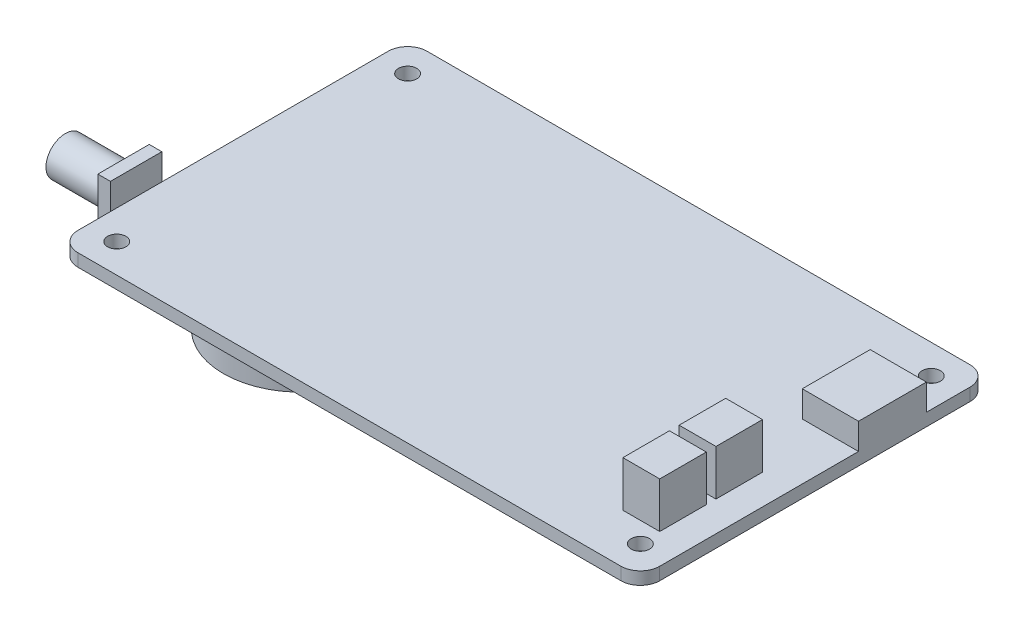
SolidWorks part; units mm, degrees
ref_plane "Front Plane" through (0, 0, 0) normal (0, 0, 1) x (1, 0, 0)
ref_plane "Top Plane" through (0, 0, 0) normal (0, 1, 0) x (1, 0, 0)
ref_plane "Right Plane" through (0, 0, 0) normal (1, 0, 0) x (0, 0, -1)
sketch "Sketch1" plane through (0, 0, 0) normal (0, 1, 0) x (1, 0, 0)
  line L1 (-38.1, 22.86) -> (38.1, 22.86)
  line L2 (-38.1, 22.86) -> (-38.1, -22.86)
  line L3 (-38.1, -22.86) -> (38.1, -22.86)
  line L4 (38.1, 22.86) -> (38.1, -22.86)
  line L5 (-38.1, 22.86) -> (38.1, -22.86) construction
  line L6 (-38.1, -22.86) -> (38.1, 22.86) construction
  point P0 (0, 0)
  dimension "D1" = 76.2
  dimension "D2" = 45.72
extrude "Boss-Extrude1" add sketch "Sketch1" along normal mid plane 1.651
sketch "Sketch2" plane through (0, -0.8255, 0) normal (0, -1, 0) x (1, 0, 0)
  line L0 (-19.05, 22.86) -> (-19.05, -22.86) construction
  line L1 (-38.1, 22.86) -> (38.1, 22.86) construction
  line L2 (38.1, -22.86) -> (-38.1, -22.86) construction
  line L3 (-38.1, -22.86) -> (-38.1, 22.86) construction
  line L4 (-38.1, 10.16) -> (38.1, 10.16) construction
  line L5 (38.1, 22.86) -> (38.1, -22.86) construction
  circle A0 centre (-19.05, 10.16) radius 10.16
  dimension "D3" = 20.32
  dimension "D1" = 19.05
  dimension "D2" = 12.7
extrude "Boss-Extrude2" add sketch "Sketch2" along normal blind 5.08
sketch "Sketch3" plane through (-38.1, 0, 0) normal (-1, 0, 0) x (0, 0, 1)
  line L0 (-22.86, 0.8255) -> (22.86, 0.8255) construction
  line L1 (9.3345, 4.2545) -> (16.0655, 4.2545)
  line L2 (9.3345, 4.2545) -> (9.3345, -2.6035)
  line L3 (9.3345, -2.6035) -> (16.0655, -2.6035)
  line L4 (16.0655, 4.2545) -> (16.0655, -2.6035)
  line L5 (9.3345, 4.2545) -> (16.0655, -2.6035) construction
  line L6 (9.3345, -2.6035) -> (16.0655, 4.2545) construction
  line L7 (22.86, 0.8255) -> (22.86, -0.8255) construction
  point P0 (12.7, 0.8255)
  dimension "D1" = 6.731
  dimension "D2" = 6.858
  dimension "D3" = 10.16
extrude "Boss-Extrude3" add sketch "Sketch3" along normal blind 1.651
sketch "Sketch4" plane through (-39.751, 0, 0) normal (-1, 0, 0) x (0, 0, 1)
  line L0 (12.7, 4.2545) -> (12.7, -2.6035) construction
  line L1 (16.0655, 4.2545) -> (9.3345, 4.2545) construction
  line L2 (9.3345, -2.6035) -> (16.0655, -2.6035) construction
  line L3 (9.3345, 0.8255) -> (16.0655, 0.8255) construction
  line L4 (16.0655, -2.6035) -> (16.0655, 4.2545) construction
  circle A0 centre (12.7, 0.8255) radius 2.54
  dimension "D1" = 5.08
extrude "Boss-Extrude4" add sketch "Sketch4" along normal blind 7.62
sketch "Sketch5" plane through (0, 0.8255, 0) normal (0, 1, 0) x (1, 0, 0)
  line L0 (-38.1, -22.86) -> (38.1, -22.86) construction
  line L1 (29.337, -10.287) -> (34.163, -10.287)
  line L2 (29.337, -10.287) -> (29.337, -16.383)
  line L3 (29.337, -16.383) -> (34.163, -16.383)
  line L4 (34.163, -10.287) -> (34.163, -16.383)
  line L5 (29.337, -10.287) -> (34.163, -16.383) construction
  line L6 (29.337, -16.383) -> (34.163, -10.287) construction
  line L7 (38.1, -22.86) -> (38.1, 22.86) construction
  line L8 (29.337, -2.921) -> (29.337, -9.017)
  line L9 (29.337, -2.921) -> (34.163, -2.921)
  line L10 (34.163, -2.921) -> (34.163, -9.017)
  line L11 (29.337, -9.017) -> (34.163, -9.017)
  point P0 (31.75, -13.335)
  dimension "D1" = 9.525
  dimension "D2" = 6.35
  dimension "D3" = 4.826
  dimension "D4" = 6.096
  dimension "D6" = 1.27
  dimension "D5" = 2
extrude "Boss-Extrude5" add sketch "Sketch5" along normal blind 5.969 and the other way blind 2.54
sketch "Sketch6" plane through (0, 0.8255, 0) normal (0, 1, 0) x (1, 0, 0)
  line L0 (38.1, 22.86) -> (38.1, -22.86) construction
  line L1 (30.734, 14.605) -> (38.1, 14.605)
  line L2 (30.734, 14.605) -> (30.734, 5.715)
  line L3 (30.734, 5.715) -> (38.1, 5.715)
  line L4 (38.1, 14.605) -> (38.1, 5.715)
  line L5 (30.734, 14.605) -> (38.1, 5.715) construction
  line L6 (30.734, 5.715) -> (38.1, 14.605) construction
  line L7 (38.1, 22.86) -> (-38.1, 22.86) construction
  point P0 (34.417, 10.16)
  dimension "D1" = 8.89
  dimension "D2" = 7.366
  dimension "D3" = 12.7
extrude "Boss-Extrude6" add sketch "Sketch6" along normal blind 3.429
sketch "Sketch7" plane through (0, 0.8255, 0) normal (0, 1, 0) x (1, 0, 0)
  line L0 (-38.1, 0) -> (38.1, 0) construction
  line L1 (-38.1, 22.86) -> (-38.1, -9.3345) construction
  line L2 (38.1, -22.86) -> (38.1, 5.715) construction
  line L3 (0, 22.86) -> (0, -22.86) construction
  line L4 (38.1, 22.86) -> (-38.1, 22.86) construction
  line L5 (-38.1, -22.86) -> (38.1, -22.86) construction
  point P0 (-34.29, 19.05)
  point P1 (-34.29, -19.05)
  point P2 (34.29, -19.05)
  point P3 (34.29, 19.05)
  dimension "D1" = 38.1
  dimension "D2" = 68.58
hole_wizard "M2 Clearance Hole1" positions "Sketch8" profile "Sketch10" hole size "M2" standard "ANSI Metric" end condition up to next
sketch "Sketch8" plane through (0, 0.8255, 0) normal (0, 1, 0) x (1, 0, 0)
  point P0 (-34.29, 19.05)
  point P5 (34.29, 19.05)
  point P8 (-34.29, -19.05)
  point P11 (34.29, -19.05)
sketch "Sketch10" plane through (-34.29, 0.8255, -19.05) normal (1, 0, 0) x (0, 0, 1)
  line L0 (0, 0) -> (0, 1.651)
  line L1 (0, 1.651) -> (1.2, 1.651)
  line L2 (1.2, 1.651) -> (1.2, 0)
  line L5 (1.2, 0) -> (0, 0)
  line L11 (0, -6.35) -> (0, 107.95) construction
  dimension "Thru Hole Dia." = 2.4
  dimension "Thru Hole Depth" = 1.651
fillet "Fillet1" radius 2.54 4 edges at (-38.1, 0, -22.86) (-38.1, 0, 22.86) (38.1, 0, 22.86) (38.1, 0, -22.86)
